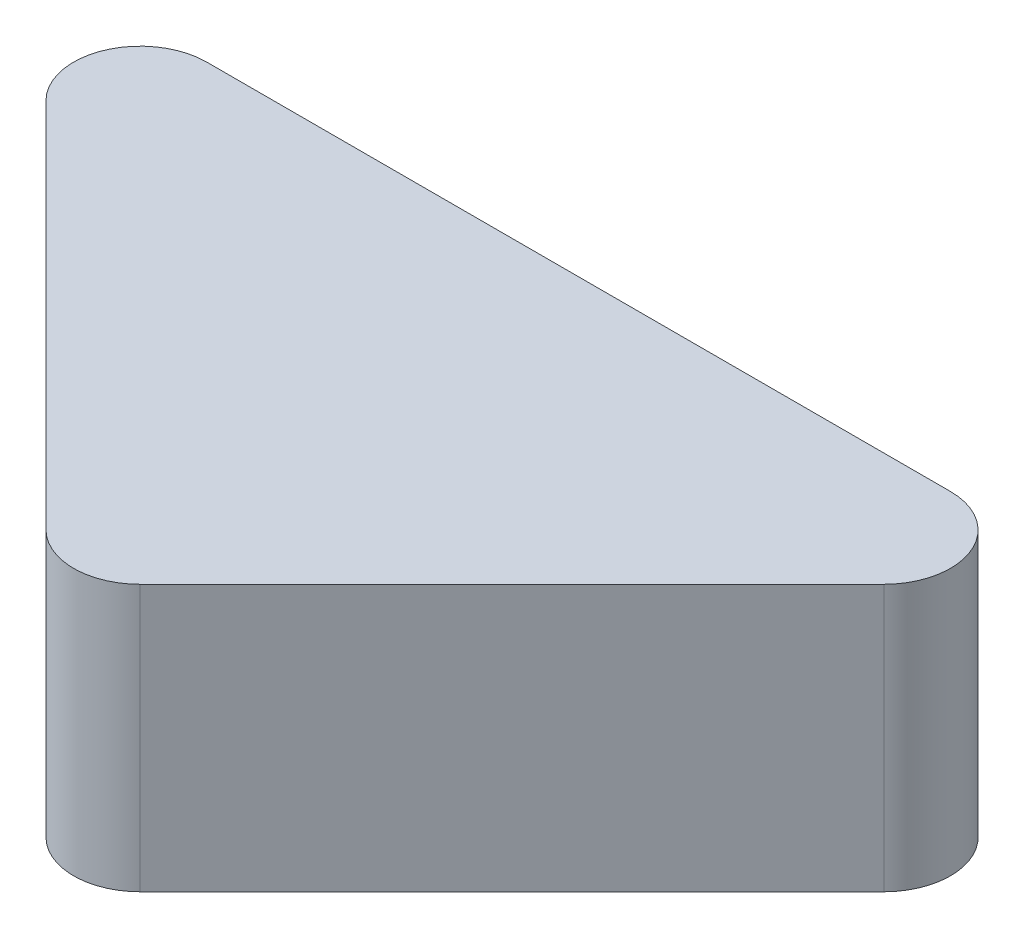
SolidWorks part; units mm, degrees
ref_plane "Front Plane" through (0, 0, 0) normal (0, 0, 1) x (1, 0, 0)
ref_plane "Top Plane" through (0, 0, 0) normal (0, 1, 0) x (1, 0, 0)
ref_plane "Right Plane" through (0, 0, 0) normal (1, 0, 0) x (0, 0, -1)
sketch "Sketch1" plane through (0, 0, 0) normal (0, 1, 0) x (1, 0, 0)
  line L0 (0, 0) -> (50.8, 50.8)
  line L1 (0, 0) -> (-50.8, 50.8)
  line L2 (-50.8, 50.8) -> (50.8, 50.8)
  dimension "D1" = 50.8
extrude "Boss-Extrude1" add sketch "Sketch1" along normal blind 25.4
fillet "Fillet1" radius 6.35 3 edges at (-50.8, 12.7, -50.8) (50.8, 12.7, -50.8) (0, 12.7, 0)
